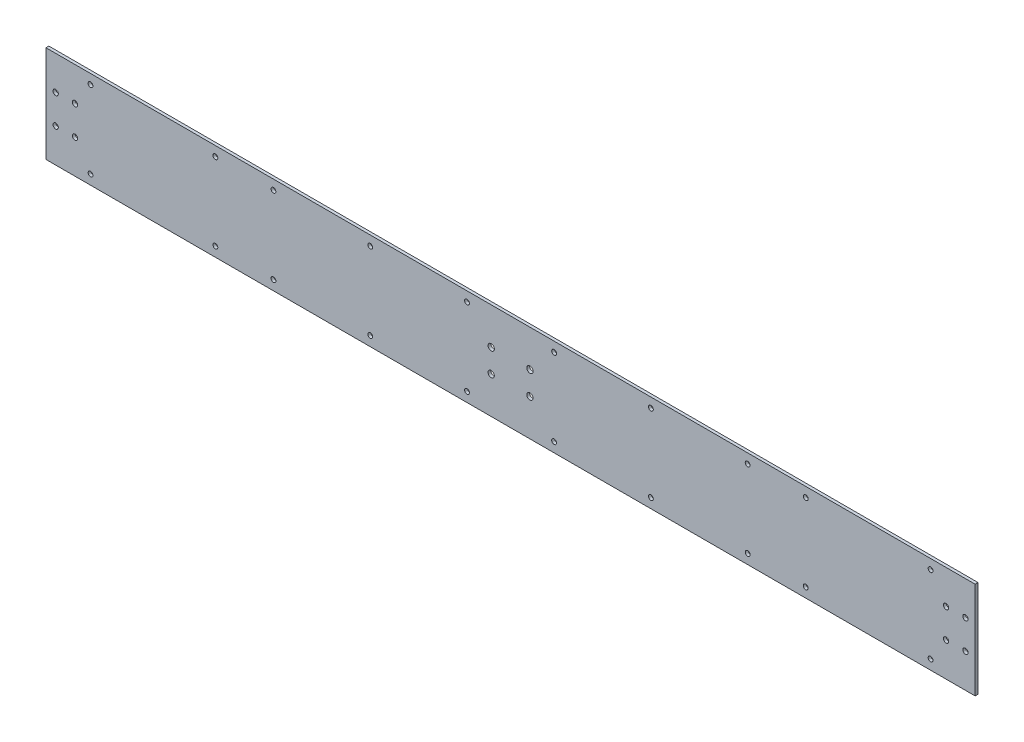
SolidWorks part; units mm, degrees
material "1.0037 (S235JR)"
ref_plane "Ebene vorne" through (0, 0, 0) normal (0, 0, 1) x (1, 0, 0)
ref_plane "Ebene oben" through (0, 0, 0) normal (0, 1, 0) x (1, 0, 0)
ref_plane "Ebene rechts" through (0, 0, 0) normal (1, 0, 0) x (0, 0, -1)
sketch "Skizze1" plane through (0, 0, 0) normal (0, 0, 1) x (1, 0, 0)
  line L0 (0, 0) -> (0, -173.7819) construction
  line L2 (-480, 0) -> (480, 0)
  line L3 (-480, 0) -> (-480, -100)
  line L4 (-480, -100) -> (480, -100)
  line L5 (480, 0) -> (480, -100)
  dimension "D1" = 100
  dimension "D2" = 960
extrude "Aufsatz-Linear austragen1" add sketch "Skizze1" along normal blind 3
sketch "Skizze2" plane through (0, 0, 3) normal (0, 0, 1) x (1, 0, 0)
  line L0 (0, 0) -> (0, -147.7559) construction
  line L1 (-480, -50) -> (480, -50) construction
  line L2 (-480, 0) -> (-480, -100) construction
  line L4 (480, -100) -> (480, 0) construction
  circle A4 centre (20, -38) radius 3.25
  circle A5 centre (-20, -38) radius 3.25
  circle A6 centre (20, -62) radius 3.25
  circle A7 centre (-20, -62) radius 3.25
  dimension "D2" = 24
  dimension "D3" = 6.5
  dimension "D1" = 40
extrude "Schnitt-Linear austragen1" cut sketch "Skizze2" against normal blind 10
sketch "Skizze3" plane through (0, 0, 3) normal (0, 0, 1) x (1, 0, 0)
  line L0 (0, 0) -> (0, -161.1472) construction
  line L1 (480, -50) -> (411.4033, -50) construction
  line L2 (480, -100) -> (480, 0) construction
  line L3 (470, -35) -> (450, -35) construction
  circle A0 centre (470, -35) radius 2.75
  circle A1 centre (450, -35) radius 2.75
  circle A2 centre (450, -65) radius 2.75
  circle A3 centre (470, -65) radius 2.75
  circle A4 centre (-470, -65) radius 2.75
  circle A5 centre (-450, -65) radius 2.75
  circle A6 centre (-470, -35) radius 2.75
  circle A7 centre (-450, -35) radius 2.75
  dimension "D4" = 5.5
  dimension "D1" = 10
  dimension "D2" = 20
  dimension "D3" = 30
extrude "Schnitt-Linear austragen2" cut sketch "Skizze3" against normal blind 10
sketch "Skizze4" plane through (0, 0, 3) normal (0, 0, 1) x (1, 0, 0)
  line L0 (455.3138, -10) -> (-53.5527, -10) construction
  line L1 (0, 0) -> (0, 113.8193) construction
  line L2 (0, 0) -> (0, -100) construction
  line L3 (-480, -100) -> (480, -100) construction
  line L4 (480, -100) -> (480, 0) construction
  line L5 (480, 0) -> (-480, 0) construction
  line L6 (0, -50) -> (517.794, -50) construction
  circle A0 centre (434, -10) radius 2.5
  circle A1 centre (305, -10) radius 2.5
  circle A2 centre (245, -10) radius 2.5
  circle A3 centre (145, -10) radius 2.5
  circle A4 centre (45, -10) radius 2.5
  circle A5 centre (434, -90) radius 2.5
  circle A6 centre (305, -90) radius 2.5
  circle A7 centre (245, -90) radius 2.5
  circle A8 centre (145, -90) radius 2.5
  circle A9 centre (45, -90) radius 2.5
  circle A10 centre (-434, -90) radius 2.5
  circle A11 centre (-434, -10) radius 2.5
  circle A12 centre (-305, -90) radius 2.5
  circle A13 centre (-305, -10) radius 2.5
  circle A14 centre (-245, -90) radius 2.5
  circle A15 centre (-245, -10) radius 2.5
  circle A16 centre (-145, -90) radius 2.5
  circle A17 centre (-145, -10) radius 2.5
  circle A18 centre (-45, -10) radius 2.5
  circle A19 centre (-45, -90) radius 2.5
  dimension "D1" = 100
  dimension "D2" = 100
  dimension "D3" = 60
  dimension "D4" = 46
  dimension "D5" = 175
  dimension "D6" = 5
  dimension "D7" = 10
extrude "Schnitt-Linear austragen6" cut sketch "Skizze4" against normal blind 10
